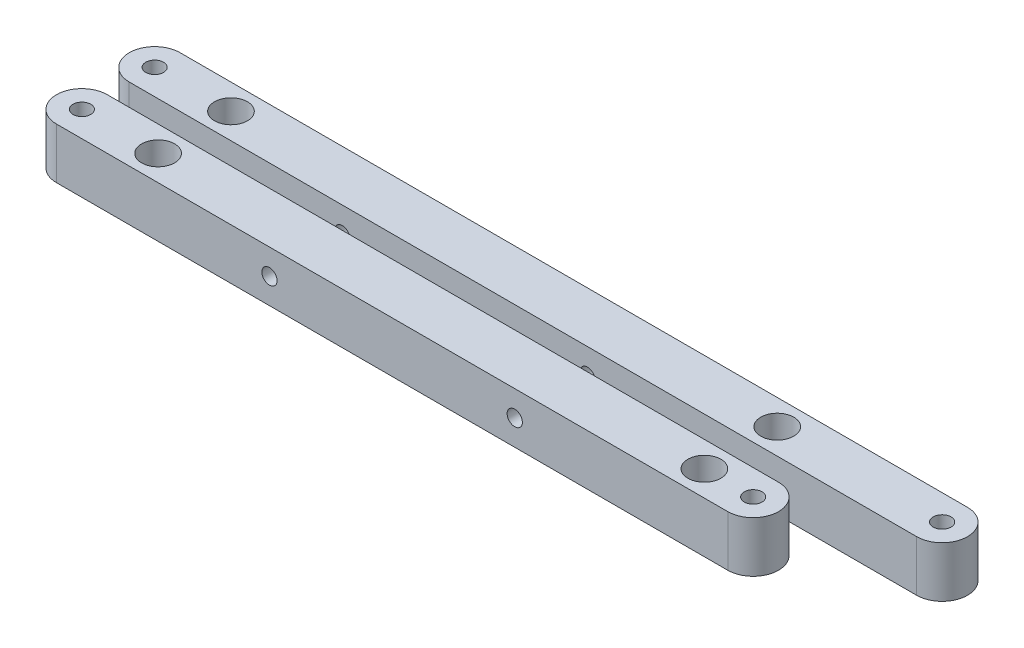
SolidWorks part; units mm, degrees
ref_plane "Front Plane" through (0, 0, 0) normal (0, 0, 1) x (1, 0, 0)
ref_plane "Top Plane" through (0, 0, 0) normal (0, 1, 0) x (1, 0, 0)
ref_plane "Right Plane" through (0, 0, 0) normal (1, 0, 0) x (0, 0, -1)
sketch "Sketch1" plane through (0, 0, 0) normal (0, 1, 0) x (1, 0, 0)
  line L0 (16.9517, 13.7915) -> (171.8917, 13.7915) construction
  line L1 (139.4317, 13.8103) -> (31.9517, 13.8103) construction
  line L2 (16.9517, -0.5273) -> (149.0317, -0.5273) construction
  line L3 (139.4317, -0.5273) -> (31.9517, -0.5273) construction
  line L4 (31.9517, 13.8103) -> (31.9517, -0.5273) construction
  line L5 (16.9517, -0.5273) -> (31.9517, -0.5273) construction
  line L6 (16.9517, 13.7915) -> (31.9517, 13.8103) construction
  line L8 (16.9517, 18.7915) -> (171.8917, 18.7915)
  line L9 (171.8917, 8.7915) -> (16.9517, 8.7915)
  line L10 (16.9517, 4.4727) -> (149.0317, 4.4727)
  line L11 (149.0317, -5.5273) -> (16.9517, -5.5273)
  circle A9 centre (16.9517, 13.7915) radius 1.75
  circle A10 centre (31.9517, 13.8103) radius 1.75
  circle A11 centre (139.4317, 13.8103) radius 1.75
  circle A12 centre (171.8917, 13.7915) radius 1.75
  circle A13 centre (16.9517, -0.5273) radius 1.75
  circle A14 centre (31.9517, -0.5273) radius 1.75
  circle A15 centre (139.4317, -0.5273) radius 1.75
  circle A16 centre (149.0317, -0.5273) radius 1.75
  arc A17 (16.9517, 18.7915) -> (16.9517, 8.7915) centre (16.9517, 13.7915) ccw
  arc A18 (16.9517, 4.4727) -> (16.9517, -5.5273) centre (16.9517, -0.5273) ccw
  arc A19 (171.8917, 18.7915) -> (171.8917, 8.7915) centre (171.8917, 13.7915) cw
  arc A20 (149.0317, 4.4727) -> (149.0317, -5.5273) centre (149.0317, -0.5273) cw
  dimension "D2" = 3.5
  dimension "D3" = 3.5
  dimension "D4" = 3.5
  dimension "D6" = 107.48
  dimension "D8" = 3.5
  dimension "D9" = 3.5
  dimension "D11" = 3.5
  dimension "D12" = 107.48
  dimension "D5" = 3.5
  dimension "D10" = 3.5
  dimension "D1" = 154.94
  dimension "D7" = 132.08
  dimension "D13" = 90
  dimension "D14" = 15
  dimension "D15" = 15
extrude "Boss-Extrude1" add sketch "Sketch1" along normal blind 10
sketch "Sketch2" plane through (0, 0, 5.5273) normal (0, 0, 1) x (1, 0, 0)
  line L0 (82.9917, 10) -> (82.9917, 0) construction
  line L1 (16.9517, 10) -> (149.0317, 10) construction
  line L2 (16.9517, 0) -> (149.0317, 0) construction
  line L3 (82.9917, 0) -> (58.8617, 0) construction
  line L4 (58.8617, 0) -> (58.8617, 10) construction
  line L5 (82.9917, 0) -> (107.1217, 0) construction
  line L6 (107.1217, 0) -> (107.1217, 10) construction
  circle A0 centre (58.8617, 5) radius 1.5
  circle A1 centre (107.1217, 5) radius 1.5
  dimension "D3" = 3
  dimension "D4" = 3
  dimension "D1" = 24.13
  dimension "D2" = 24.13
extrude "Cut-Extrude1" cut sketch "Sketch2" against normal through all
ref_plane "Plane1" through (171.8917, 0, -8.7915) normal (0, -1, 0) x (-1, 0, 0)
sketch "Sketch4" plane through (0, 10, 0) normal (0, 1, 0) x (1, 0, 0)
  circle A0 centre (31.9517, 13.8103) radius 3.25
  circle A1 centre (31.9517, -0.5273) radius 3.25
  circle A2 centre (139.4317, -0.5273) radius 3.25
  circle A3 centre (139.4317, 13.8103) radius 3.25
  dimension "D1" = 6.5
  dimension "D2" = 6.5
  dimension "D3" = 6.5
  dimension "D4" = 6.5
extrude "Cut-Extrude2" cut sketch "Sketch4" against normal blind 8
